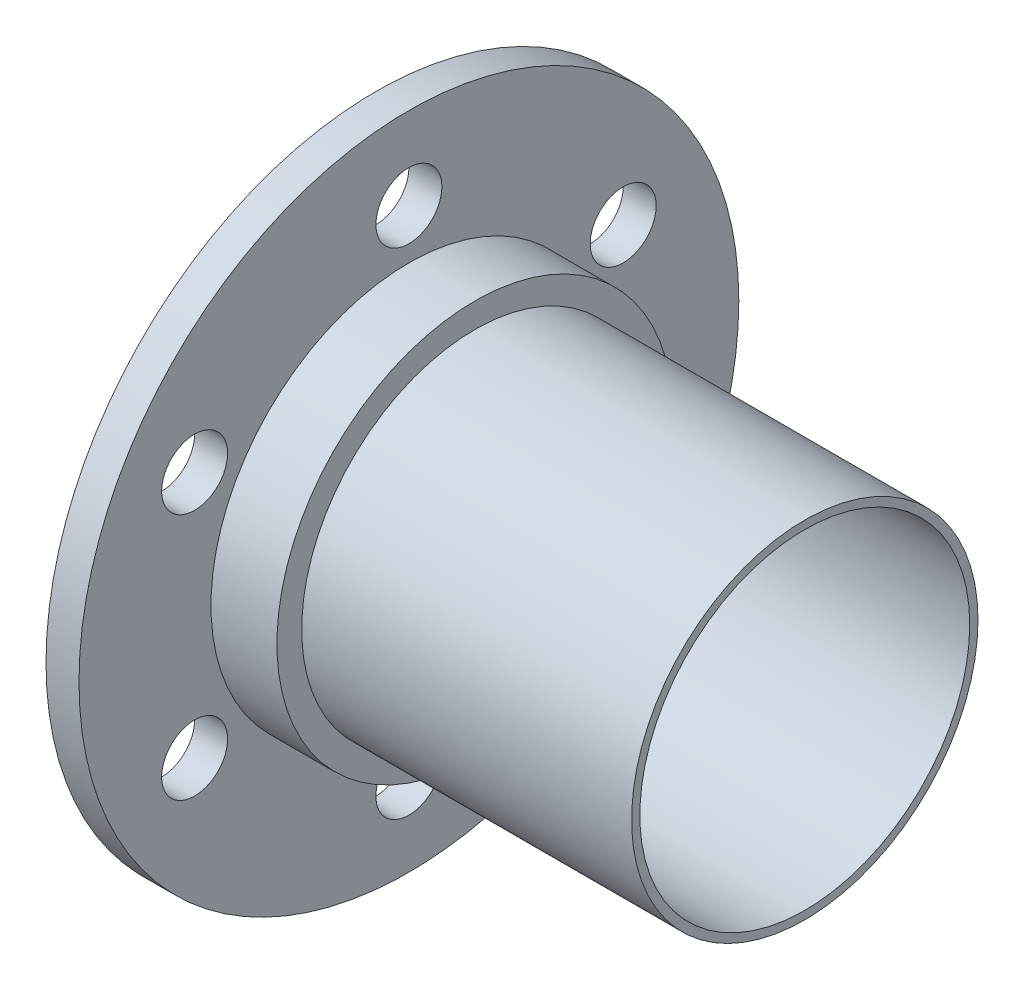
SolidWorks part; units mm, degrees
ref_plane "Front Plane" through (0, 0, 0) normal (0, 0, 1) x (1, 0, 0)
ref_plane "Top Plane" through (0, 0, 0) normal (0, 1, 0) x (1, 0, 0)
ref_plane "Right Plane" through (0, 0, 0) normal (1, 0, 0) x (0, 0, -1)
sketch "Sketch1" plane through (0, 0, 0) normal (1, 0, 0) x (0, 0, -1)
  line L2 (0, 55) -> (0, -55) construction
  circle A0 centre (0, 0) radius 52.5
  circle A1 centre (0, 0) radius 100
  circle A2 centre (0, 75) radius 10
  circle A3 centre (64.9519, 37.5) radius 10
  circle A4 centre (64.9519, -37.5) radius 10
  circle A5 centre (0, -75) radius 10
  circle A6 centre (-64.9519, -37.5) radius 10
  circle A7 centre (-64.9519, 37.5) radius 10
  point P21 (0, 0)
  dimension "D1" = 105
  dimension "D2" = 200
  dimension "D4" = 20
  dimension "D3" = 75
  dimension "D5" = 6
extrude "Boss-Extrude1" add sketch "Sketch1" against normal blind 10
sketch "Sketch2" plane through (0, 0, 0) normal (1, 0, 0) x (0, 0, -1)
  circle A0 centre (0, 0) radius 60
  circle A1 centre (0, 0) radius 52.5
  dimension "D1" = 105
  dimension "D2" = 120
extrude "Boss-Extrude2" add sketch "Sketch2" along normal blind 20
sketch "Sketch3" plane through (20, 0, 0) normal (1, 0, 0) x (0, 0, -1)
  circle A0 centre (0, 0) radius 52.5
  circle A1 centre (0, 0) radius 50
  dimension "D1" = 100
  dimension "D2" = 105
extrude "Boss-Extrude3" add sketch "Sketch3" along normal blind 100 separate body
